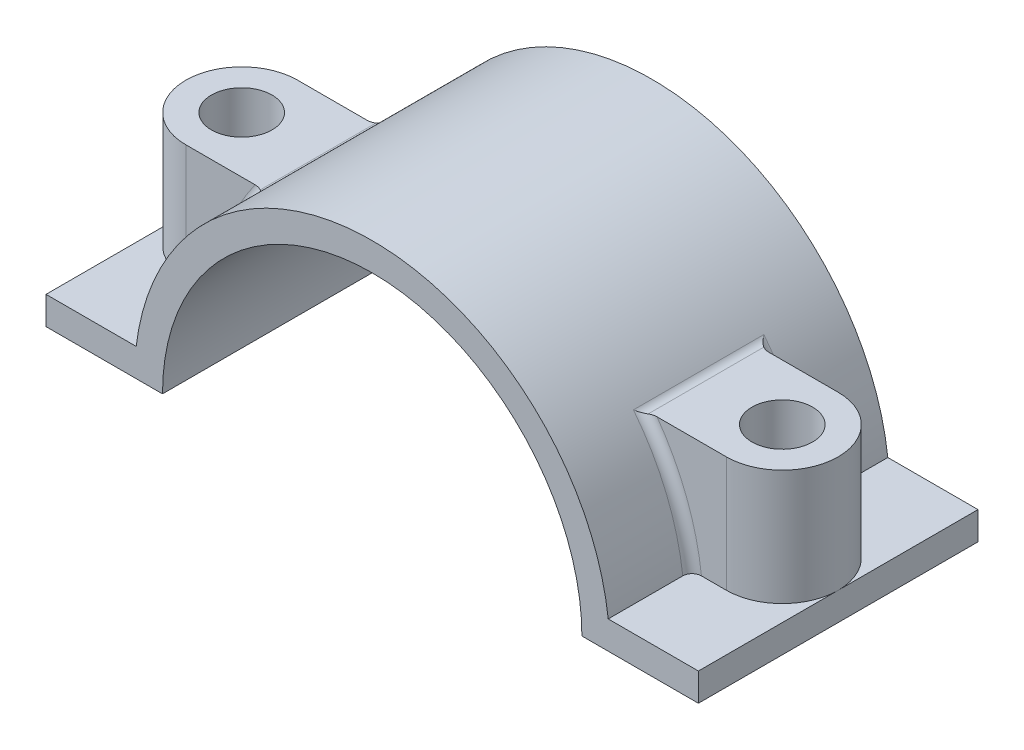
SolidWorks part; units mm, degrees
ref_plane "Front Plane" through (0, 0, 0) normal (0, 0, 1) x (1, 0, 0)
ref_plane "Top Plane" through (0, 0, 0) normal (0, 1, 0) x (1, 0, 0)
ref_plane "Right Plane" through (0, 0, 0) normal (1, 0, 0) x (0, 0, -1)
sketch "Sketch1" plane through (0, 0, 0) normal (0, 0, 1) x (1, 0, 0)
  line L0 (-22.5, 0) -> (-35, 0)
  line L1 (-35, 0) -> (-35, 3)
  line L2 (-35, 3) -> (-25.3229, 3)
  line L3 (22.5, 0) -> (35, 0)
  line L4 (35, 0) -> (35, 3)
  line L5 (35, 3) -> (25.3229, 3)
  arc A0 (22.5, 0) -> (-22.5, 0) centre (0, 0) ccw
  arc A1 (25.3229, 3) -> (-25.3229, 3) centre (0, 0) ccw
  dimension "D1" = 3
  dimension "D5" = 25.5
  dimension "D2" = 70
  dimension "D3" = 3
  dimension "D4" = 3
extrude "Boss-Extrude1" add sketch "Sketch1" along normal mid plane 30
ref_plane "Plane1" through (0, 15.4, 0) normal (0, 1, 0) x (1, 0, 0)
sketch "Sketch2" plane through (0, 15.4, 0) normal (0, 1, 0) x (1, 0, 0)
  line L0 (-20.12, 6) -> (-20.12, -6)
  line L1 (-20.12, -6) -> (-29, -6)
  line L2 (-20.12, 6) -> (-29, 6)
  line L3 (-35, -15) -> (-35, 15) construction
  arc A0 (-29, 6) -> (-29, -6) centre (-29, 0) ccw
  point P2 (-20.12, 0)
  point P7 (-35, 0)
  dimension "D1" = 6
  dimension "D2" = 8.88
extrude "Boss-Extrude2" add sketch "Sketch2" against normal up to body separate body
sketch "Sketch3" plane through (0, 15.4, 0) normal (0, 1, 0) x (1, 0, 0)
  circle A0 centre (-29, 0) radius 3.25
extrude "Cut-Extrude1" cut sketch "Sketch3" against normal through all
mirror "Mirror1" about plane through (0, 0, 0) normal (1, 0, 0) of "Cut-Extrude1", "Boss-Extrude2"
fillet "Fillet1" radius 1 3 edges at (23.6509, 9.5334, -6) (23.6509, 9.5334, 6) (20.3246, 15.4, 0)
fillet "Fillet2" radius 1 3 edges at (-23.6509, 9.5334, -6) (-23.6509, 9.5334, 6) (-20.3246, 15.4, 0)
